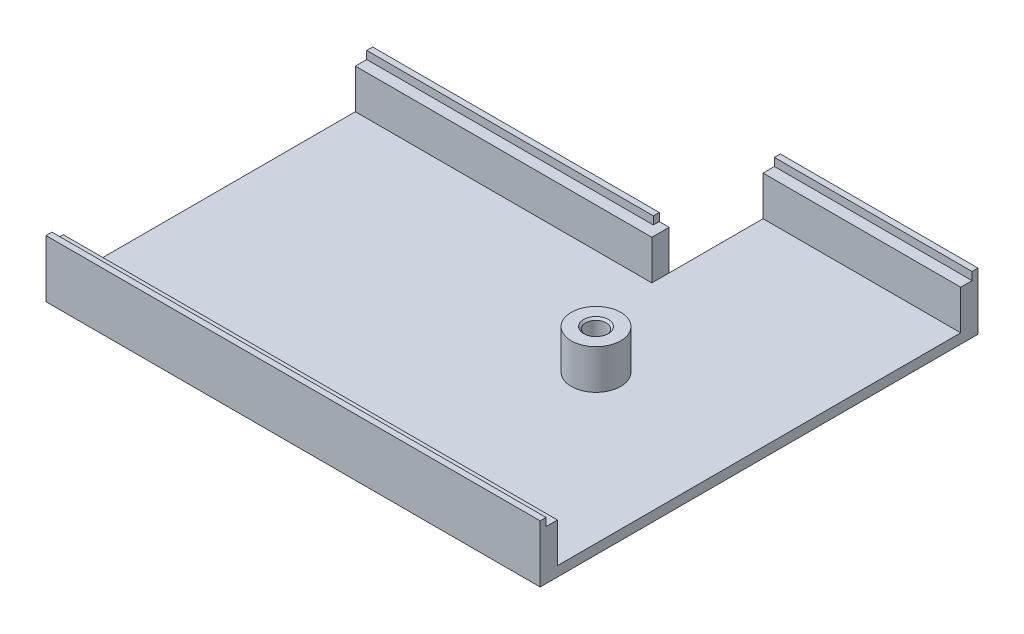
SolidWorks part; units mm, degrees
ref_plane "Ebene vorne" through (0, 0, 0) normal (0, 0, 1) x (1, 0, 0)
ref_plane "Ebene oben" through (0, 0, 0) normal (0, 1, 0) x (1, 0, 0)
ref_plane "Ebene rechts" through (0, 0, 0) normal (1, 0, 0) x (0, 0, -1)
sketch "Skizze1" plane through (0, 0, 0) normal (0, 1, 0) x (1, 0, 0)
  line L5 (0, 66.1) -> (0, 0)
  line L6 (0, 0) -> (100, 0)
  line L7 (100, 0) -> (100, 88.6)
  line L8 (100, 88.6) -> (60, 88.6)
  line L9 (60, 88.6) -> (60, 66.1)
  line L10 (60, 66.1) -> (0, 66.1)
  dimension "D5" = 100
  dimension "D6" = 66.1
  dimension "D7" = 88.6
  dimension "D8" = 40
extrude "Aufsatz-Linear austragen1" add sketch "Skizze1" along normal blind 2
sketch "Skizze2" plane through (0, 2, 0) normal (0, 1, 0) x (1, 0, 0)
  line L0 (100, 0) -> (100, 88.6) construction
  line L1 (0, 66.1) -> (60, 66.1)
  line L2 (0, 66.1) -> (0, 62.6)
  line L3 (0, 62.6) -> (60, 62.6)
  line L4 (60, 66.1) -> (60, 62.6)
  line L5 (0, 66.1) -> (60, 62.6) construction
  line L6 (0, 62.6) -> (60, 66.1) construction
  line L7 (60, 88.6) -> (100, 88.6)
  line L8 (60, 88.6) -> (60, 85.1)
  line L9 (60, 85.1) -> (100, 85.1)
  line L10 (100, 88.6) -> (100, 85.1)
  line L11 (60, 88.6) -> (100, 85.1) construction
  line L12 (60, 85.1) -> (100, 88.6) construction
  line L13 (60, 88.6) -> (60, 66.1) construction
  line L14 (0, 0) -> (100, 0)
  line L15 (0, 0) -> (0, 3.5)
  line L16 (0, 3.5) -> (100, 3.5)
  line L17 (100, 0) -> (100, 3.5)
  line L18 (0, 0) -> (100, 3.5) construction
  line L19 (0, 3.5) -> (100, 0) construction
  line L20 (0, 66.1) -> (0, 0) construction
  circle A0 centre (70, 41.3) radius 5
  point P4 (30, 64.35)
  point P10 (80, 86.85)
  point P18 (50, 1.75)
  dimension "D4" = 10
  dimension "D1" = 3.5
  dimension "D2" = 70
  dimension "D3" = 41.3
extrude "Aufsatz-Linear austragen2" add sketch "Skizze2" along normal blind 8
sketch "Skizze3" plane through (0, 10, 0) normal (0, 1, 0) x (1, 0, 0)
  circle A0 centre (70, 41.3) radius 2.1
  dimension "D1" = 4.2
extrude "Schnitt-Linear austragen1" cut sketch "Skizze3" against normal blind 9
chamfer "Fase1" distance 0.4 angle 45 1 edges at (70, 10, -39.2)
sketch "Skizze4" plane through (0, 10, 0) normal (0, 1, 0) x (1, 0, 0)
  line L1 (0, 66.1) -> (58, 66.1)
  line L2 (0, 66.1) -> (0, 64.9)
  line L3 (0, 64.9) -> (58, 64.9)
  line L4 (58, 66.1) -> (58, 64.9)
  line L5 (0, 66.1) -> (58, 64.9) construction
  line L6 (0, 64.9) -> (58, 66.1) construction
  line L11 (100, 85.1) -> (100, 88.6) construction
  line L12 (60, 88.6) -> (100, 88.6)
  line L18 (60, 88.6) -> (60, 87.4)
  line L19 (60, 87.4) -> (100, 87.4)
  line L21 (100, 88.6) -> (100, 87.4)
  line L22 (60, 88.6) -> (100, 87.4) construction
  line L23 (60, 87.4) -> (100, 88.6) construction
  line L24 (100, 0) -> (100, 3.5) construction
  line L25 (0, 0) -> (100, 0)
  line L26 (0, 0) -> (0, 1.2)
  line L27 (0, 1.2) -> (100, 1.2)
  line L28 (100, 0) -> (100, 1.2)
  line L29 (0, 0) -> (100, 1.2) construction
  line L30 (0, 1.2) -> (100, 0) construction
  point P4 (29, 65.5)
  point P10 (80, 88)
  point P20 (50, 0.6)
  dimension "D1" = 1.2
  dimension "D2" = 58
extrude "Aufsatz-Linear austragen3" add sketch "Skizze4" along normal blind 1.6
